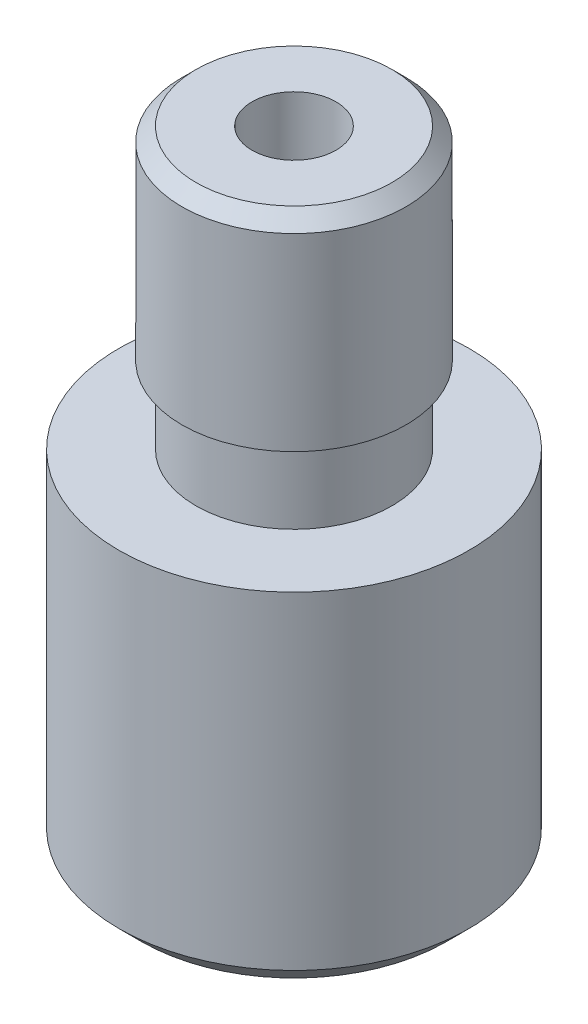
SolidWorks part; units mm, degrees
ref_plane "Спереди" through (0, 0, 0) normal (0, 0, 1) x (1, 0, 0)
ref_plane "Сверху" through (0, 0, 0) normal (0, 1, 0) x (1, 0, 0)
ref_plane "Справа" through (0, 0, 0) normal (1, 0, 0) x (0, 0, -1)
sketch "Эскиз1" plane through (0, 0, 0) normal (0, 0, 1) x (1, 0, 0)
  line L0 (0, 36.6102) -> (0, -51.8644) construction
  line L1 (3, -30.5085) -> (12.5, -30.5085)
  line L2 (12.5, -30.5085) -> (12.5, -5.5085)
  line L3 (12.5, -5.5085) -> (7, -5.5085)
  line L4 (7, -5.5085) -> (7, 0)
  line L5 (7, 0) -> (8, 0)
  line L6 (8, 0) -> (8, 14.4915)
  line L7 (8, 14.4915) -> (3, 14.4915)
  line L8 (3, 14.4915) -> (3, -30.5085)
  dimension "D1" = 45
  dimension "D2" = 25
  dimension "D3" = 16
  dimension "D4" = 25
  dimension "D5" = 14
  dimension "D6" = 6
revolve "Повернуть1" add sketch "Эскиз1" angle 360 about L0
chamfer "Фаска1" distance 1.6 angle 45 1 edges at (0, -30.5085, 12.5)
chamfer "Фаска2" distance 1 angle 45 1 edges at (0, 14.4915, 8)
